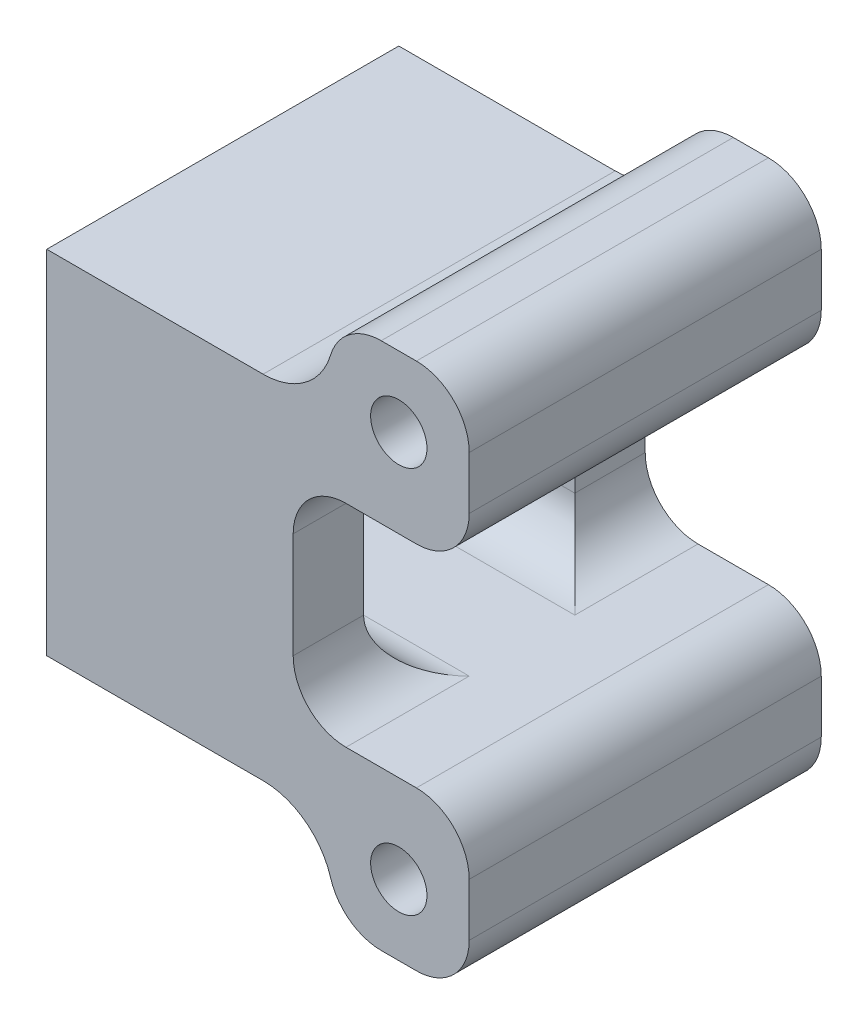
SolidWorks part; units mm, degrees
ref_plane "Front" through (0, 0, 0) normal (0, 0, 1) x (1, 0, 0)
ref_plane "Top" through (0, 0, 0) normal (0, 1, 0) x (1, 0, 0)
ref_plane "Right" through (0, 0, 0) normal (1, 0, 0) x (0, 0, -1)
sketch "Sketch1" plane through (0, 0, 0) normal (1, 0, 0) x (0, 0, -1)
  line L1 (0, 0) -> (-20, 0)
  line L2 (0, 0) -> (0, -20)
  line L3 (0, -20) -> (-20, -20)
  line L4 (-20, 0) -> (-20, -20)
  dimension "D1" = 20
  dimension "D2" = 20
extrude "Boss-Extrude1" add sketch "Sketch1" along normal blind 4
sketch "Sketch2" plane through (4, 0, 0) normal (1, 0, 0) x (0, 0, -1)
  line L0 (0, -20) -> (0, 0) construction
  line L1 (-20, -20) -> (0, -20) construction
  circle A0 centre (-10, -10) radius 3.7
  dimension "D1" = 7.4
  dimension "D2" = 10
  dimension "D3" = 10
extrude "Cut-Extrude1" cut sketch "Sketch2" against normal blind 2.6
sketch "Sketch3" plane through (1.4, 0, 0) normal (1, 0, 0) x (0, 0, -1)
  circle A0 centre (-10, -10) radius 2.1
  dimension "D1" = 4.2
extrude "Cut-Extrude2" cut sketch "Sketch3" against normal through all
sketch "Sketch4" plane through (4, 0, 0) normal (1, 0, 0) x (0, 0, -1)
  line L0 (0, 0) -> (-20, 0) construction
  line L1 (-20, -20) -> (-16, -20)
  line L2 (-20, -20) -> (-20, 0)
  line L3 (-20, 0) -> (-16, 0)
  line L4 (-16, -20) -> (-16, 0)
  line L5 (0, -20) -> (0, 0) construction
  line L6 (-16, 0) -> (0, 0)
  line L7 (-16, 0) -> (-16, -4)
  line L8 (-16, -4) -> (0, -4)
  line L9 (0, 0) -> (0, -4)
  line L10 (-20, -20) -> (0, -20) construction
  line L11 (0, -4) -> (-4, -4)
  line L12 (0, -4) -> (0, -20)
  line L13 (0, -20) -> (-4, -20)
  line L14 (-4, -4) -> (-4, -20)
  line L16 (-4, -20) -> (-16, -20)
  line L17 (-4, -20) -> (-4, -16)
  line L18 (-4, -16) -> (-16, -16)
  line L19 (-16, -20) -> (-16, -16)
  line M6 (0, -20) -> (0, 0)
  line M7 (0, 0) -> (-20, 0)
  line M8 (-20, 0) -> (-20, -20)
  line M9 (-20, -20) -> (0, -20)
  dimension "D1" = 4
  dimension "D2" = 4
  dimension "D3" = 4
  dimension "D4" = 4
extrude "Boss-Extrude2" add sketch "Sketch4" along normal blind 10 contours L4 M9 M7 M8 | L14 L18 L4 M9 | L8 L14 M9 M6 | L4 L8 M6 M7
sketch "Sketch7" plane through (14, 0, 0) normal (1, 0, 0) x (0, 0, -1)
  line L0 (-20, 0) -> (-20, -20) construction
  line L1 (0, -20) -> (-20, -20)
  line L2 (0, -20) -> (0, -16)
  line L3 (0, -16) -> (-20, -16)
  line L4 (-20, -20) -> (-20, -16)
  line L6 (0, 0) -> (-20, 0)
  line L7 (0, 0) -> (0, -4)
  line L8 (0, -4) -> (-20, -4)
  line L9 (-20, 0) -> (-20, -4)
  dimension "D1" = 4
  dimension "D2" = 4
extrude "Boss-Extrude3" add sketch "Sketch7" along normal blind 10
sketch "Sketch8" plane through (0, -20, 0) normal (0, -1, 0) x (-1, 0, 0)
  line L0 (-24, -20) -> (0, -20) construction
  line L1 (-24, 0) -> (-16, 0)
  line L2 (-24, 0) -> (-24, -20)
  line L3 (-24, -20) -> (-16, -20)
  line L4 (-16, 0) -> (-16, -20)
  dimension "D1" = 8
extrude "Boss-Extrude4" add sketch "Sketch8" along normal blind 5
sketch "Sketch9" plane through (0, 0, 0) normal (0, 1, 0) x (1, 0, 0)
  line L0 (24, -20) -> (0, -20) construction
  line L1 (24, 0) -> (16, 0)
  line L2 (24, 0) -> (24, -20)
  line L3 (24, -20) -> (16, -20)
  line L4 (16, 0) -> (16, -20)
  dimension "D1" = 8
extrude "Boss-Extrude5" add sketch "Sketch9" along normal blind 5
sketch "Sketch10" plane through (0, 0, 0) normal (0, 0, -1) x (-1, 0, 0)
  line L0 (-24, -4) -> (-14, -4) construction
  line L1 (-24, -4) -> (-24, 5) construction
  line L3 (-24, 5) -> (-16, 5) construction
  circle A0 centre (-20, 1) radius 1.6
  circle A1 centre (-20, -21) radius 1.6
  dimension "D1" = 3.2
  dimension "D2" = 5
  dimension "D3" = 4
  dimension "D4" = 2
extrude "Cut-Extrude5" cut sketch "Sketch10" against normal through all
fillet "Fillet6" radius 3 6 edges at (16, 5, 10) (24, 5, 10) (24, -4, 10) (16, -25, 10) (24, -16, 10) (24, -25, 10)
fillet "Fillet7" radius 3 8 edges at (14, -16, 2) (14, -16, 18) (14, -4, 18) (14, -4, 2) (9, -16, 4) (9, -16, 16) (9, -4, 4) (9, -4, 16)
fillet "Fillet8" radius 4 2 edges at (16, -20, 10) (16, 0, 10)
